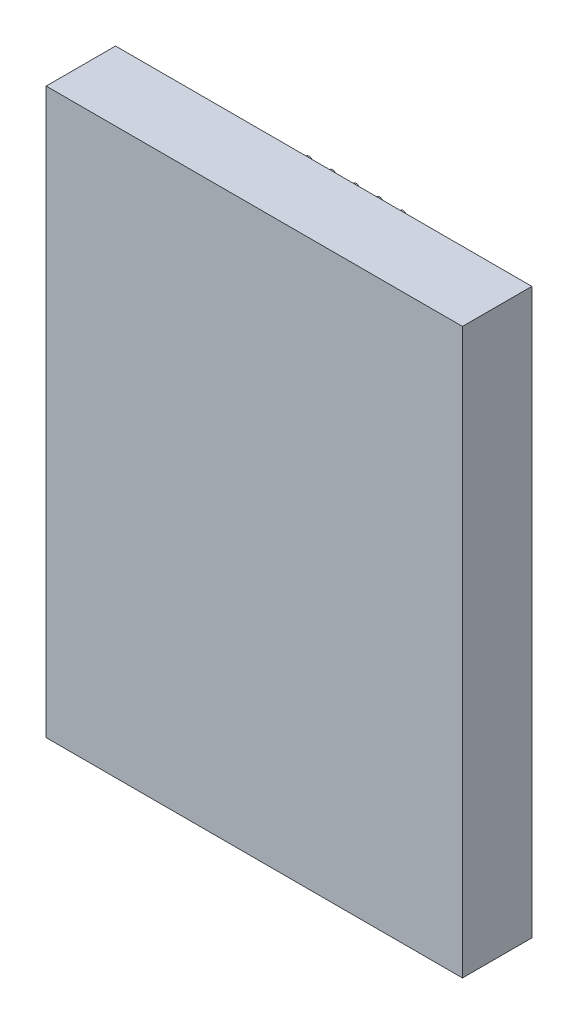
SolidWorks part; units mm, degrees
ref_plane "Alzado" through (0, 0, 0) normal (0, 0, 1) x (1, 0, 0)
ref_plane "Planta" through (0, 0, 0) normal (0, 1, 0) x (1, 0, 0)
ref_plane "Vista lateral" through (0, 0, 0) normal (1, 0, 0) x (0, 0, -1)
sketch "Croquis1" plane through (0, 0, 0) normal (0, 0, 1) x (1, 0, 0)
  line L1 (-45, 61) -> (45, 61)
  line L2 (-45, 61) -> (-45, -61)
  line L3 (-45, -61) -> (45, -61)
  line L4 (45, 61) -> (45, -61)
  line L5 (-45, 61) -> (45, -61) construction
  line L6 (-45, -61) -> (45, 61) construction
  point P0 (0, 0)
  dimension "D1" = 90
  dimension "D2" = 122
extrude "Saliente-Extruir1" add sketch "Croquis1" along normal blind 15
sketch "Croquis2" plane through (0, 0, 0) normal (0, 0, 1) x (1, 0, 0)
  line L0 (45, -61) -> (45, 61) construction
  line L2 (10.16, 53.5) -> (10.16, -53.5) construction
  line L3 (-12.7616, 0) -> (36.3779, 0) construction
  circle A0 centre (10.16, -53.5) radius 0.8
  circle A1 centre (10.16, 53.5) radius 0.8
  circle A2 centre (5.08, -53.5) radius 0.8
  circle A3 centre (5.08, 53.5) radius 0.8
  circle A4 centre (0, -53.5) radius 0.8
  circle A5 centre (0, 53.5) radius 0.8
  circle A6 centre (-5.08, -53.5) radius 0.8
  circle A7 centre (-5.08, 53.5) radius 0.8
  circle A8 centre (-10.16, -53.5) radius 0.8
  circle A9 centre (-10.16, 53.5) radius 0.8
  point P6 (10.16, 0)
  dimension "D1" = 1.6
  dimension "D2" = 34.84
  dimension "D3" = 107
  dimension "D4" = 5
extrude "Saliente-Extruir2" add sketch "Croquis2" against normal blind 7
